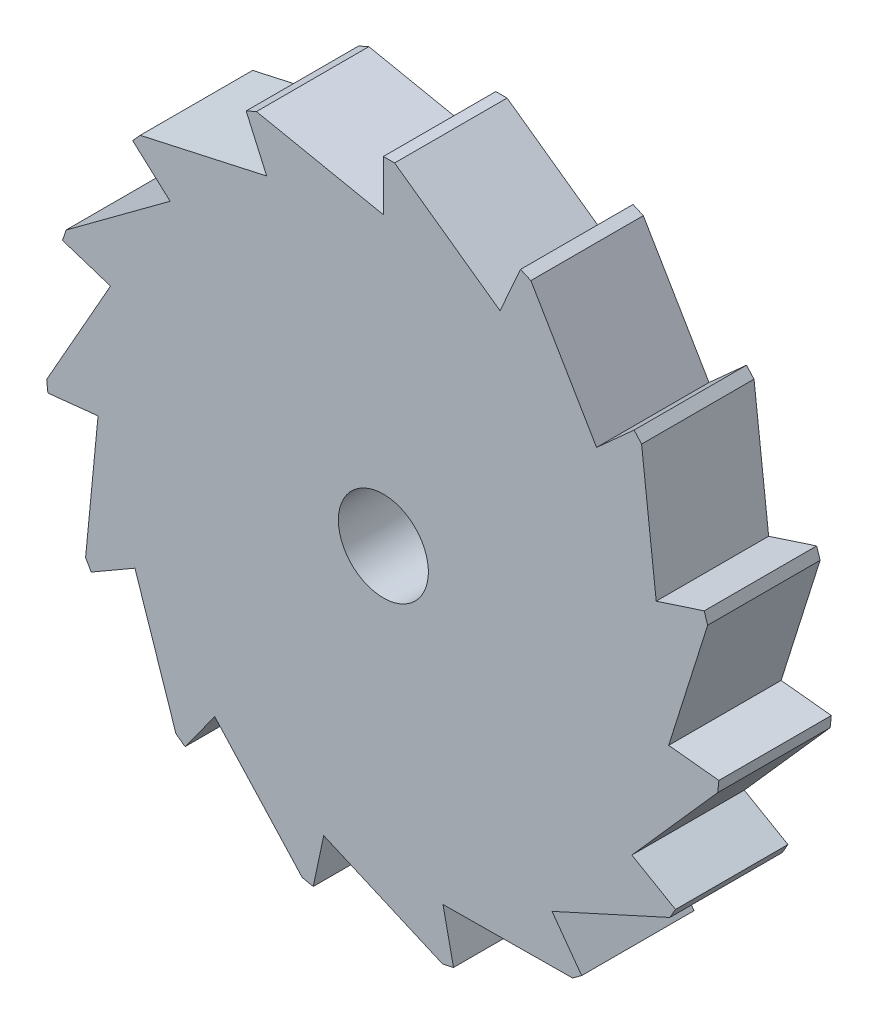
SolidWorks part; units mm, degrees
ref_plane "Front Plane" through (0, 0, 0) normal (0, 0, 1) x (1, 0, 0)
ref_plane "Top Plane" through (0, 0, 0) normal (0, 1, 0) x (1, 0, 0)
ref_plane "Right Plane" through (0, 0, 0) normal (1, 0, 0) x (0, 0, -1)
sketch "Sketch1" plane through (0, 0, 0) normal (0, 0, 1) x (1, 0, 0)
  line L0 (0, 25.5126) -> (0, 30)
  line L1 (0, 30) -> (1.0009, 30)
  line L2 (1.0009, 30) -> (10.3769, 23.307)
  line L3 (13.1165, 26.9993) -> (18.9596, 17.0713)
  line L4 (10.3769, 23.307) -> (12.2021, 27.4064)
  line L5 (12.2021, 27.4064) -> (13.1165, 26.9993)
  line L6 (22.9641, 19.3301) -> (24.264, 7.8838)
  line L7 (18.9596, 17.0713) -> (22.2943, 20.0739)
  line L8 (22.2943, 20.0739) -> (22.9641, 19.3301)
  line L9 (28.841, 8.3186) -> (25.3729, -2.6668)
  line L10 (24.264, 7.8838) -> (28.5317, 9.2705)
  line L11 (28.5317, 9.2705) -> (28.841, 8.3186)
  line L12 (29.731, -4.1313) -> (22.0946, -12.7563)
  line L13 (25.3729, -2.6668) -> (29.8357, -3.1359)
  line L14 (29.8357, -3.1359) -> (29.731, -4.1313)
  line L15 (25.4803, -15.8668) -> (14.996, -20.6402)
  line L16 (22.0946, -12.7563) -> (25.9808, -15)
  line L17 (25.9808, -15) -> (25.4803, -15.8668)
  line L18 (16.8238, -24.8588) -> (5.3044, -24.9551)
  line L19 (14.996, -20.6402) -> (17.6336, -24.2705)
  line L20 (17.6336, -24.2705) -> (16.8238, -24.8588)
  line L21 (5.2583, -29.5525) -> (-5.3044, -24.9551)
  line L22 (5.3044, -24.9551) -> (6.2374, -29.3444)
  line L23 (6.2374, -29.3444) -> (5.2583, -29.5525)
  line L24 (-7.2164, -29.1363) -> (-14.996, -20.6402)
  line L25 (-5.3044, -24.9551) -> (-6.2374, -29.3444)
  line L26 (-6.2374, -29.3444) -> (-7.2164, -29.1363)
  line L27 (-18.4433, -23.6822) -> (-22.0946, -12.7563)
  line L28 (-14.996, -20.6402) -> (-17.6336, -24.2705)
  line L29 (-17.6336, -24.2705) -> (-18.4433, -23.6822)
  line L30 (-26.4812, -14.1332) -> (-25.3729, -2.6668)
  line L31 (-22.0946, -12.7563) -> (-25.9808, -15)
  line L32 (-25.9808, -15) -> (-26.4812, -14.1332)
  line L33 (-29.9403, -2.1404) -> (-24.264, 7.8838)
  line L34 (-25.3729, -2.6668) -> (-29.8357, -3.1359)
  line L35 (-29.8357, -3.1359) -> (-29.9403, -2.1404)
  line L36 (-28.2224, 10.2224) -> (-18.9596, 17.0713)
  line L37 (-24.264, 7.8838) -> (-28.5317, 9.2705)
  line L38 (-28.5317, 9.2705) -> (-28.2224, 10.2224)
  line L39 (-21.6246, 20.8177) -> (-10.3769, 23.307)
  line L40 (-18.9596, 17.0713) -> (-22.2943, 20.0739)
  line L41 (-22.2943, 20.0739) -> (-21.6246, 20.8177)
  line L42 (-11.2877, 27.8135) -> (0, 25.5126)
  line L43 (-10.3769, 23.307) -> (-12.2021, 27.4064)
  line L44 (-12.2021, 27.4064) -> (-11.2877, 27.8135)
  line L45 (0, 0) -> (14.3091, 20.5) construction
  circle A0 centre (0, 0) radius 25 construction
  circle A1 centre (0, 0) radius 4
  dimension "D1" = 50
  dimension "D8" = 8
  dimension "D2" = 4.4874
  dimension "D3" = 1.0009
  dimension "D4" = 25.5126
  dimension "D6" = 25
  dimension "D7" = 10.3769
  dimension "D5" = 15
extrude "Boss-Extrude2" add sketch "Sketch1" along normal blind 10 contours L9 L13 L14 L12 L16 L17 L15 L19 L20 L18 L22 L23 L21 L25 L26 L24 L28 L29 L27 L31 L32 L30 L34 L35 L33 L37 L38 L36 L40 L41 L39 L43 L44 L42 L0 L1 L2 L4 L5 L3 L7 L8 L6 L10 L11
sketch "Sketch2" plane through (0, 0, 0) normal (0, 0, -1) x (-1, 0, 0)
  circle A0 centre (0, 0) radius 4
  dimension "D1" = 8
extrude "Cut-Extrude1" cut sketch "Sketch2" against normal blind 10
